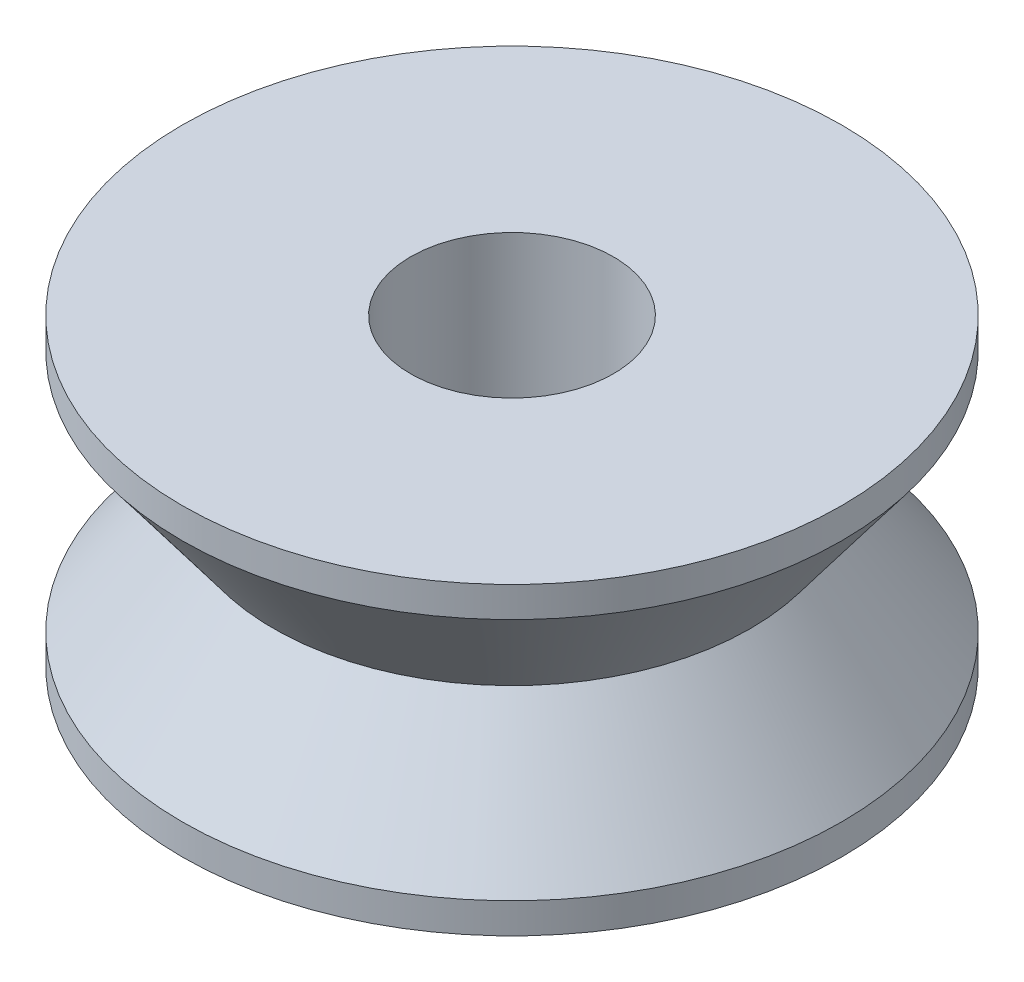
SolidWorks part; units mm, degrees
ref_plane "正面" through (0, 0, 0) normal (0, 0, 1) x (1, 0, 0)
ref_plane "平面" through (0, 0, 0) normal (0, 1, 0) x (1, 0, 0)
ref_plane "右側面" through (0, 0, 0) normal (1, 0, 0) x (0, 0, -1)
sketch "ｽｹｯﾁ1" plane through (0, 0, 0) normal (0, 0, 1) x (1, 0, 0)
  line L0 (0, -3) -> (0, 3)
  line L1 (6.5, 3) -> (6.5, 2.4)
  line L2 (0, 3) -> (6.5, 3)
  line L3 (0, 3) -> (0, -3)
  line L4 (0, -3) -> (6.5, -3)
  line L5 (6.5, 3) -> (6.5, -3) construction
  line L6 (6.5, -3) -> (6.5, -2.4)
  line L7 (6.5, 0) -> (4.7, 0) construction
  line L8 (6.5, 2.4) -> (4.7, 0)
  line L9 (4.7, 0) -> (6.5, -2.4)
  point P2 (0, 0)
  point P11 (0, 0)
  dimension "D1" = 6
  dimension "D2" = 6.5
  dimension "D3" = 0.6
  dimension "D4" = 0.6
  dimension "D5" = 1.8
revolve "回転1" add sketch "ｽｹｯﾁ1" angle 360 about L0
sketch "ｽｹｯﾁ2" plane through (0, 3, 0) normal (0, 1, 0) x (1, 0, 0)
  circle A0 centre (0, 0) radius 2
  dimension "D1" = 4
extrude "ｶｯﾄ - 押し出し1" cut sketch "ｽｹｯﾁ2" against normal blind 10
